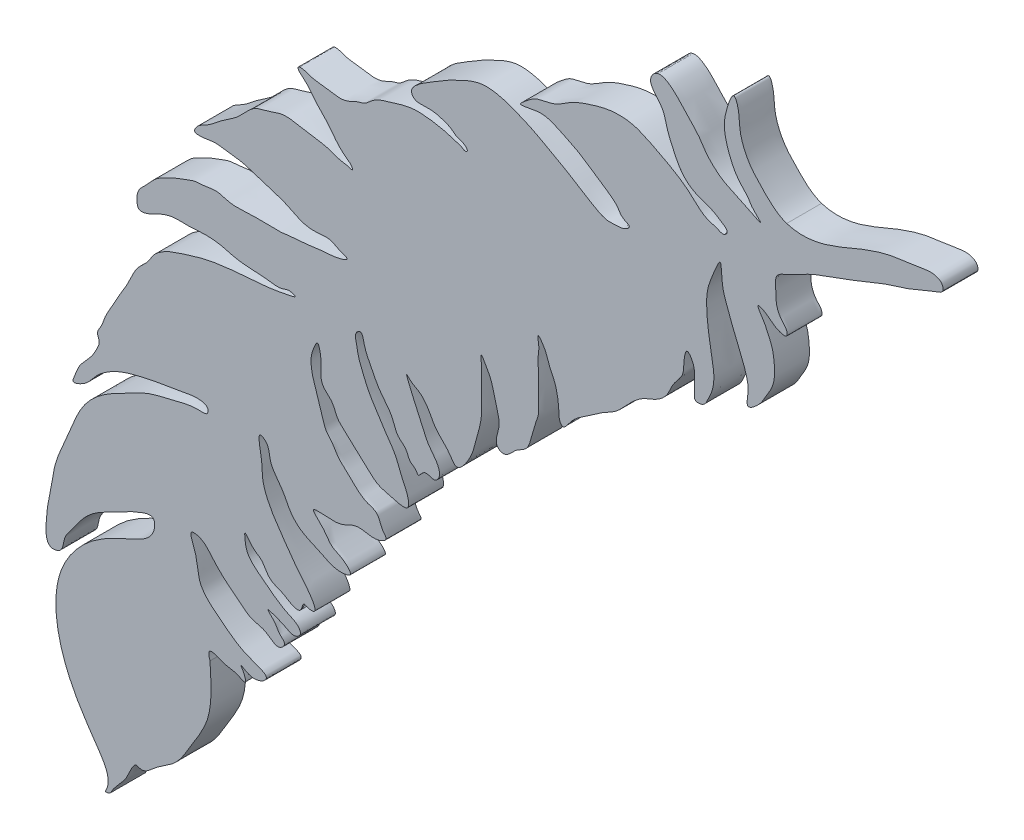
SolidWorks part; units mm, degrees
ref_plane "Front Plane" through (0, 0, 0) normal (0, 0, 1) x (1, 0, 0)
ref_plane "Top Plane" through (0, 0, 0) normal (0, 1, 0) x (1, 0, 0)
ref_plane "Right Plane" through (0, 0, 0) normal (1, 0, 0) x (0, 0, -1)
sketch "Sketch1" plane through (0, 0, 0) normal (0, 0, 1) x (1, 0, 0)
  spline S0 degree 3 poles (-130.9467, -108.1029) (-128.844, -104.5303) (-133.2229, -98.0617) (-140.4387, -87.7664) (-145.7431, -74.402) (-144.8577, -58.4947) (-135.4551, -46.9899) (-124.8632, -42.3321) (-116.6652, -38.5269) (-116.711, -32.2964) (-123.1018, -34.4185) (-127.8508, -37.3502) (-136.151, -41.0642) (-139.7124, -46.8951) (-143.0554, -51.1178) (-142.7943, -54.7815) (-148.1158, -56.0793) (-147.8976, -45.4367) (-146.7832, -42.0452) (-145.8145, -36.7315) knots 0 0 0 0 0.071999 0.142329 0.261516 0.352989 0.452069 0.539533 0.596776 0.612555 0.63935 0.692715 0.747246 0.811375 0.828147 0.855447 0.872397 0.912939 1 1 1 1
  spline S1 degree 3 poles (-145.8145, -36.7315) (-145.2425, -32.4211) (-141.6427, -25.7022) (-138.331, -16.0665) (-132.2062, -9.8358) (-125.3081, -6.4139) (-118.6118, -2.6719) (-110.9551, -1.2423) (-106.0581, 0.35) (-101.4791, -0.1016) (-101.3307, 2.2835) (-104.8015, 3.0909) (-109.3012, 2.0954) (-115.5816, 1.1564) (-121.7598, -0.1618) (-127.9715, -1.9517) (-133.8317, -5.7378) (-135.9952, -9.7491) (-140.7434, -11.5272) (-139.2788, -8.2299) (-138.3199, -5.5232) (-135.0871, -2.591) (-133.4145, 0.3391) (-132.3422, 2.8136) (-133.651, 4.7964) (-131.7557, 6.9934) (-131.1378, 9.849) (-128.8798, 13.2765) (-127.2356, 16.7899) (-124.8277, 20.4246) (-123.4034, 23.5527) (-121.5888, 27.0955) (-118.7401, 29.1021) (-117.3166, 32.0143) (-114.9372, 34.0308) (-112.2226, 35.3878) (-108.4974, 36.6034) (-104.884, 37.7861) (-98.7946, 39.2465) (-92.1613, 39.7967) (-85.1409, 40.2715) (-80.3905, 41.0184) (-78.0627, 41.5241) (-75.7765, 42.0261) (-78.3281, 42.9738) (-80.9565, 41.4526) (-85.626, 42.6465) (-90.4373, 42.5565) (-94.3652, 43.1754) (-97.6294, 44.2358) (-100.8618, 44.5773) (-104.4744, 44.5748) (-107.7007, 44.1631) (-111.4229, 44.4812) (-115.3716, 43.3867) (-118.3428, 41.3586) (-121.5769, 40.9448) (-122.0593, 43.8636) (-121.4517, 46.3592) (-119.2461, 48.2316) (-117.6236, 50.2677) (-115.5114, 52.0927) (-113.115, 53.1259) (-110.6816, 54.4299) (-107.8714, 55.3392) (-105.2832, 56.4738) (-102.1693, 56.4135) (-99.0898, 57.3489) (-95.3021, 55.7924) (-91.9956, 55.8287) (-88.5031, 56.0876) (-85.6184, 56.0415) (-82.4696, 55.9327) (-79.7537, 56.0001) (-76.4322, 56.5953) (-72.7137, 56.6345) (-67.8471, 57.5558) (-64.6895, 57.3733) (-60.4663, 59.0206) (-64.2107, 59.8982) (-66.5803, 61.7329) (-70.7806, 60.7203) (-75.3991, 61.6706) (-79.2318, 64.0422) (-83.8103, 65.3217) (-87.7823, 66.6072) (-91.8542, 68.0259) (-95.4883, 68.163) (-99.4198, 69.0258) (-101.871, 68.3328) (-105.7516, 68.1743) (-104.4989, 70.8074) (-101.1447, 72.0079) (-97.4031, 75.6233) (-92.1887, 78.4725) (-88.8776, 83.3667) (-84.1157, 84.0674) (-79.4215, 86.1522) (-73.3235, 84.433) (-67.5899, 84.0308) (-63.4361, 82.1793) (-61.6259, 82.1884) (-59.7973, 81.4721) (-60.3689, 82.8864) (-61.9782, 83.8593) (-64.5646, 86.23) (-67.1184, 90.0416) (-70.569, 93.1372) (-72.7879, 96.4652) (-74.7394, 97.9434) (-75.5485, 98.8186) (-75.7842, 99.8266) (-73.1491, 99.6116) (-71.7069, 98.706) (-68.7481, 98.5034) (-66.1793, 98.0981) (-63.5382, 97.6556) (-60.9534, 98.0927) (-58.9672, 99.4185) (-56.3276, 99.8815) (-53.821, 102.6861) (-48.7243, 104.1339) (-43.1357, 105.8664) (-38.5572, 105.5244) (-34.8476, 104.9701) (-32.082, 104.228) (-29.8504, 103.4942) (-28.5749, 103.0724) (-27.8017, 102.4148) (-26.54, 103.0555) (-28.6101, 104.6958) (-30.2671, 104.8456) (-31.7005, 106.2624) (-34.0734, 107.1873) (-36.7949, 107.9962) (-39.7383, 107.8714) (-42.0713, 107.7728) (-43.7368, 110.0644) (-40.3855, 113.3243) (-36.931, 115.0605) (-32.7938, 117.7502) (-28.4708, 119.7962) (-22.4533, 122.3952) (-14.8974, 120.5825) (-8.1853, 117.6005) (-1.8695, 113.9762) (4.175, 110.6904) (9.0581, 107.2618) (12.9429, 105.513) (15.7739, 105.8325) (17.7076, 105.7686) (20.1716, 107.5455) (17.0875, 108.3967) (16.1324, 110.7817) (12.9117, 113.2266) (9.1289, 115.6519) (4.7977, 118.7333) (0.6747, 120.6622) (-3.5001, 122.5643) (-6.824, 123.1594) (-13.3839, 121.2933) (-9.7101, 124.1753) (-7.3105, 126.1829) (-1.9208, 126.4847) (2.6848, 130.2871) (7.892, 131.998) (13.819, 133.7568) (19.8315, 133.8518) (25.7451, 131.0689) (31.1696, 128.2798) (36.7597, 124.7845) (40.7165, 120.3489) (44.3063, 119.738) (46.4126, 118.5249) (48.0425, 120.3235) (45.4359, 121.9361) (42.6387, 123.8833) (37.9758, 124.8621) (34.0507, 128.3632) (32.0767, 132.5931) (30.0748, 136.9753) (29.256, 142.0798) (26.0994, 144.2887) (25.546, 146.1618) knots 0 0 0 0 0.018062 0.032075 0.042446 0.053932 0.064471 0.074799 0.085752 0.088563 0.090359 0.09344 0.100907 0.110977 0.119788 0.12761 0.138522 0.146809 0.149918 0.152475 0.157498 0.164086 0.169478 0.172249 0.174621 0.178162 0.182689 0.187179 0.195196 0.19913 0.205526 0.209752 0.215717 0.21971 0.223159 0.22867 0.232435 0.239705 0.244719 0.258871 0.267501 0.275032 0.277821 0.279495 0.281569 0.284601 0.293371 0.299581 0.305358 0.30997 0.314051 0.319012 0.325222 0.327703 0.334762 0.341688 0.343535 0.346796 0.351241 0.354536 0.358574 0.362332 0.36614 0.369542 0.373965 0.378645 0.381214 0.38703 0.391622 0.397914 0.400813 0.406435 0.410074 0.414128 0.417882 0.424267 0.429938 0.438041 0.440075 0.444068 0.447026 0.454302 0.459767 0.46698 0.472993 0.479765 0.484683 0.491021 0.495277 0.500764 0.504218 0.505631 0.51084 0.519174 0.527113 0.535889 0.542321 0.546583 0.557287 0.567308 0.571413 0.575467 0.57631 0.577593 0.579407 0.585319 0.591439 0.598986 0.604682 0.608135 0.60926 0.609681 0.612114 0.616011 0.618595 0.62402 0.627262 0.629776 0.63489 0.637139 0.640794 0.650011 0.658916 0.66537 0.669135 0.67477 0.677463 0.678983 0.68058 0.681134 0.68413 0.686695 0.689242 0.691979 0.697513 0.700903 0.704682 0.706402 0.71145 0.719707 0.724641 0.731851 0.740139 0.751504 0.763023 0.771423 0.782201 0.791999 0.79681 0.799622 0.80366 0.805768 0.808796 0.812205 0.817004 0.825099 0.831543 0.839233 0.844608 0.850004 0.856479 0.859522 0.864039 0.871219 0.880285 0.888714 0.894109 0.906513 0.912778 0.921542 0.932252 0.940852 0.945035 0.947905 0.949663 0.952766 0.957403 0.965785 0.971471 0.97906 0.985217 0.991936 1 1 1 1
  spline S2 degree 3 poles (25.546, 146.1618) (25.1351, 147.6034) (26.7348, 149.8362) (29.4957, 149.3341) (31.0837, 148.3202) (32.7788, 146.9071) (34.446, 145.0088) (36.7154, 142.4751) (39.1282, 140.2446) (41.4161, 136.4135) (44.6439, 133.0123) (49.8159, 130.2476) (53.1171, 129.1321) (58.8201, 125.9383) (54.4308, 129.5718) (53.4289, 131.8747) (50.5569, 134.396) (48.0176, 139.0516) (46.2031, 145.553) (47.0849, 150.0517) (49.3248, 156.6709) (51.0972, 150.9581) (50.8339, 147.3568) (52.327, 142.6468) (54.4854, 139.0485) (58.4886, 134.9038) (61.4688, 131.7424) (64.5305, 130.7115) knots 0 0 0 0 0.042355 0.054881 0.07823 0.096504 0.118961 0.151481 0.195631 0.213423 0.280713 0.331135 0.373483 0.407047 0.444716 0.464039 0.488542 0.550401 0.620288 0.668347 0.710884 0.740447 0.78659 0.832748 0.876319 0.90858 1 1 1 1
  spline S3 degree 3 poles (64.5305, 130.7115) (68.4869, 129.4335) (76.0888, 130.5923) (85.803, 135.2163) (94.5872, 138.0443) (101.8912, 138.5704) (106.816, 139.7113) (109.2263, 138.0241) (109.6701, 135.9138) (107.4023, 135.1283) (104.3148, 134.0192) (99.7252, 131.812) (93.6119, 130.2137) (87.2253, 127.6113) (79.5645, 124.4272) (71.323, 121.915) (65.7444, 118.3402) (60.9863, 116.7049) (61.4897, 112.3813) (61.3444, 108.8324) (62.9459, 105.8725) (64.5853, 104.4967) (64.8039, 102.2237) (60.7347, 103.0601) (59.7106, 105.0393) (55.2704, 106.9439) (57.9828, 103.2805) (59.1303, 100.803) (60.6399, 97.3798) (61.082, 93.213) (61.0991, 88.7454) (58.5392, 84.8316) (56.9999, 81.8728) (52.6602, 78.3812) (53.4878, 82.8243) (53.5031, 85.051) (52.6461, 88.3819) (51.3084, 91.9598) (49.237, 96.5459) (47.3798, 101.8402) (45.7934, 105.753) (45.8397, 113.4829) (43.1736, 106.9559) (41.272, 102.5563) (41.6383, 94.3653) (42.9133, 87.8644) (43.8695, 82.0172) (43.2849, 78.1953) (41.7648, 75.4361) (40.9118, 73.4352) (38.0219, 73.2096) (38.0911, 76.1503) (38.008, 78.9639) (38.1486, 82.1871) (35.5284, 86.1782) (34.9345, 80.9935) (34.9405, 77.6425) (31.7435, 74.8444) (30.5239, 70.8605) (27.405, 68.1333) (23.0543, 66.8166) (19.2175, 63.5209) (15.9975, 59.4475) (11.3239, 57.2972) (6.7027, 53.7219) (3.1782, 51.7924) (0.4723, 47.5085) (-0.7441, 49.1441) (-0.7899, 51.2402) (-1.0584, 54.658) (-1.9033, 58.1256) (-3.9859, 61.9047) (-4.3121, 64.4494) (-7.2761, 68.2106) (-6.3774, 64.4949) (-7.0402, 61.3768) (-6.3595, 56.316) (-6.9073, 51.3771) (-6.4691, 47.5394) (-8.0576, 44.097) (-8.6034, 40.7342) (-10.0751, 36.9385) (-13.1687, 35.8785) (-14.7775, 33.6544) (-16.8692, 32.5509) (-19.7693, 34.4644) (-17.2085, 38.9338) (-18.9231, 43.7239) (-19.8298, 48.8112) (-21.3053, 51.5012) (-23.3687, 55.1483) (-22.7847, 50.1747) (-23.3455, 46.3054) (-22.5279, 39.2597) (-24.7511, 32.0896) (-25.7266, 26.9322) (-30.2393, 21.7894) (-32.7593, 26.4707) (-36.2826, 28.8742) (-38.1823, 33.5072) (-40.8332, 36.4529) (-43.0911, 37.2327) (-45.3155, 39.886) (-43.1831, 35.5181) (-42.2681, 32.8589) (-40.2228, 29.0782) (-38.6053, 24.2113) (-35.2076, 20.9291) (-34.9079, 17.852) (-36.51, 15.8654) (-38.7784, 17.4752) (-40.1834, 16.3244) (-41.1935, 14.9467) (-41.892, 16.7638) (-43.8513, 17.3352) (-44.3929, 20.3094) (-47.53, 22.0427) (-48.4869, 26.8314) (-52.3451, 30.4516) (-54.7133, 35.7774) (-56.5605, 38.7758) (-57.2498, 43.212) (-59.7186, 41.5498) (-58.8592, 39.5048) (-58.4563, 36.1293) (-56.954, 32.4294) (-54.93, 27.9815) (-52.4187, 24.4327) (-50.3854, 20.9114) (-47.4361, 17.1078) (-46.0661, 12.5037) (-44.1319, 9.1759) (-43.5645, 5.0913) (-47.1226, 5.5261) (-49.6647, 6.2503) (-53.1547, 7.1764) (-55.8474, 9.9124) (-59.125, 12.6971) (-61.7654, 15.3783) (-64.6744, 17.8529) (-65.4292, 21.4258) (-69.4423, 23.8685) (-68.9883, 28.7022) (-69.097, 31.3985) (-70.0238, 34.4067) (-71.9135, 30.4742) (-72.1054, 27.3058) (-70.8209, 22.1566) (-69.3632, 18.5445) (-68.4222, 15.5092) (-67.8505, 13.0843) (-65.5772, 11.0748) (-64.3049, 8.0834) (-61.157, 5.7452) (-58.7192, 2.8236) (-55.7994, 0.999) (-52.9816, 0.3836) (-52.0297, -1.926) (-51.43, -3.6189) (-49.8083, -5.1549) (-53.9148, -7.7154) (-58.0554, -5.0038) (-63.392, -8.5046) (-66.9173, -8.0673) (-72.7619, -7.8039) (-67.844, -11.5474) (-66.419, -14.9243) (-63.0223, -15.9124) (-59.3822, -19.2727) (-65.2044, -20.4205) (-68.8484, -17.7616) (-74.2072, -15.8661) (-77.8801, -12.6018) (-79.9739, -7.33) (-84.0449, -3.3103) (-83.8502, 1.2142) (-87.7376, 4.0478) (-85.6758, -3.6511) (-86.2046, -8.7704) (-83.054, -15.305) (-78.9757, -20.8564) (-75.535, -25.8572) (-72.6277, -28.9588) (-69.7085, -33.6549) (-72.5698, -33.6385) (-74.3999, -32.453) (-74.5162, -36.0106) (-77.8811, -34.9097) (-80.122, -33.0834) (-84.1091, -32.2285) (-85.8338, -27.6834) (-88.5901, -26.9974) (-91.0049, -23.1179) (-90.8183, -26.1278) (-90.3243, -29.2942) (-86.0028, -32.5821) (-82.2926, -35.5662) (-78.6428, -37.8088) (-75.8833, -38.7656) (-74.4426, -41.117) (-76.7389, -42.8408) (-79.5214, -41.182) (-81.4516, -40.4249) (-85.2865, -39.0814) (-81.8166, -41.8669) (-81.4499, -43.8318) (-78.7936, -45.5962) (-81.6252, -48.4678) (-84.7523, -44.7519) (-89.2665, -44.6388) (-92.4447, -41.488) (-96.3781, -38.7707) (-100.0754, -35.0459) (-102.727, -31.4722) (-107.3267, -30.7958) (-104.0351, -37.2958) (-104.8334, -43.4924) (-97.5456, -49.2243) (-91.819, -53.5727) (-87.6164, -54.7944) (-83.1639, -56.8222) (-88.4919, -60.1885) (-92.9284, -56.2956) (-90.9493, -58.8463) (-90.3401, -61.6615) (-93.6259, -59.5536) (-96.9573, -59.9618) (-102.3443, -56.4386) (-100.8888, -60.6327) knots 0 0 0 0 0.013574 0.024795 0.036191 0.043876 0.04994 0.051583 0.053318 0.055843 0.058096 0.06489 0.072449 0.079323 0.087898 0.100378 0.107433 0.111022 0.115152 0.119826 0.12333 0.125753 0.12713 0.129252 0.135507 0.137299 0.140866 0.143728 0.148481 0.152495 0.157915 0.163034 0.167106 0.171132 0.174224 0.177305 0.179582 0.185423 0.190172 0.196585 0.203214 0.20797 0.211732 0.218529 0.227529 0.237066 0.241226 0.247302 0.249471 0.251795 0.254452 0.255519 0.260595 0.26421 0.267175 0.271235 0.274654 0.279753 0.28379 0.288499 0.292826 0.298876 0.305072 0.309908 0.315964 0.323799 0.326427 0.327344 0.32957 0.333517 0.33875 0.341506 0.347451 0.349448 0.352201 0.354743 0.361895 0.36793 0.371738 0.374422 0.380351 0.383353 0.387339 0.39029 0.392663 0.394227 0.400409 0.405116 0.411539 0.416331 0.418383 0.420411 0.4271 0.435752 0.442146 0.45178 0.455632 0.458766 0.465672 0.470835 0.475018 0.478186 0.479483 0.483862 0.485491 0.490409 0.497394 0.502793 0.505453 0.507 0.510128 0.511907 0.513115 0.514167 0.516673 0.519684 0.522932 0.527855 0.534776 0.540407 0.546371 0.549151 0.550395 0.554131 0.55506 0.561958 0.567173 0.571454 0.576461 0.580775 0.587541 0.591744 0.59499 0.597532 0.601158 0.604748 0.609106 0.613756 0.619187 0.62177 0.626296 0.630583 0.635976 0.640159 0.641507 0.643748 0.6492 0.654916 0.660365 0.66244 0.665592 0.668425 0.672287 0.676176 0.681284 0.684939 0.687637 0.690294 0.692516 0.694101 0.696257 0.704294 0.708857 0.715221 0.718112 0.722722 0.727331 0.731326 0.735209 0.737755 0.746038 0.751007 0.756489 0.76183 0.769894 0.774247 0.776109 0.782499 0.788085 0.797341 0.804155 0.812037 0.816303 0.821157 0.82273 0.824362 0.826815 0.829772 0.832813 0.837425 0.842162 0.84649 0.849277 0.850037 0.854763 0.860667 0.866786 0.871115 0.874821 0.876596 0.878853 0.88187 0.886116 0.888046 0.890883 0.894352 0.896693 0.898916 0.903763 0.90888 0.913689 0.917994 0.925032 0.931067 0.932876 0.93759 0.946119 0.956434 0.964841 0.969947 0.972394 0.977804 0.981392 0.983344 0.985764 0.987791 0.992403 1 1 1 1
  spline S4 degree 3 poles (-100.8888, -60.6327) (-100.6269, -65.4333) (-99.7964, -74.323) (-106.0262, -83.6781) (-110.2662, -91.5062) (-116.2738, -94.2536) (-119.7877, -98.174) (-122.2129, -96.8245) (-123.8813, -99.1631) (-125.0196, -103.0055) (-128.4167, -105.5721) (-129.3998, -107.6785) knots 0 0 0 0 0.255621 0.413057 0.567957 0.683936 0.763554 0.779621 0.806758 0.880983 1 1 1 1
  spline S5 degree 2 poles (-129.3998, -107.6785) (-130.0612, -108.3073) (-130.9467, -108.1029) knots 0 0 0 1 1 1
extrude "Boss-Extrude1" add sketch "Sketch1" along normal blind 10
